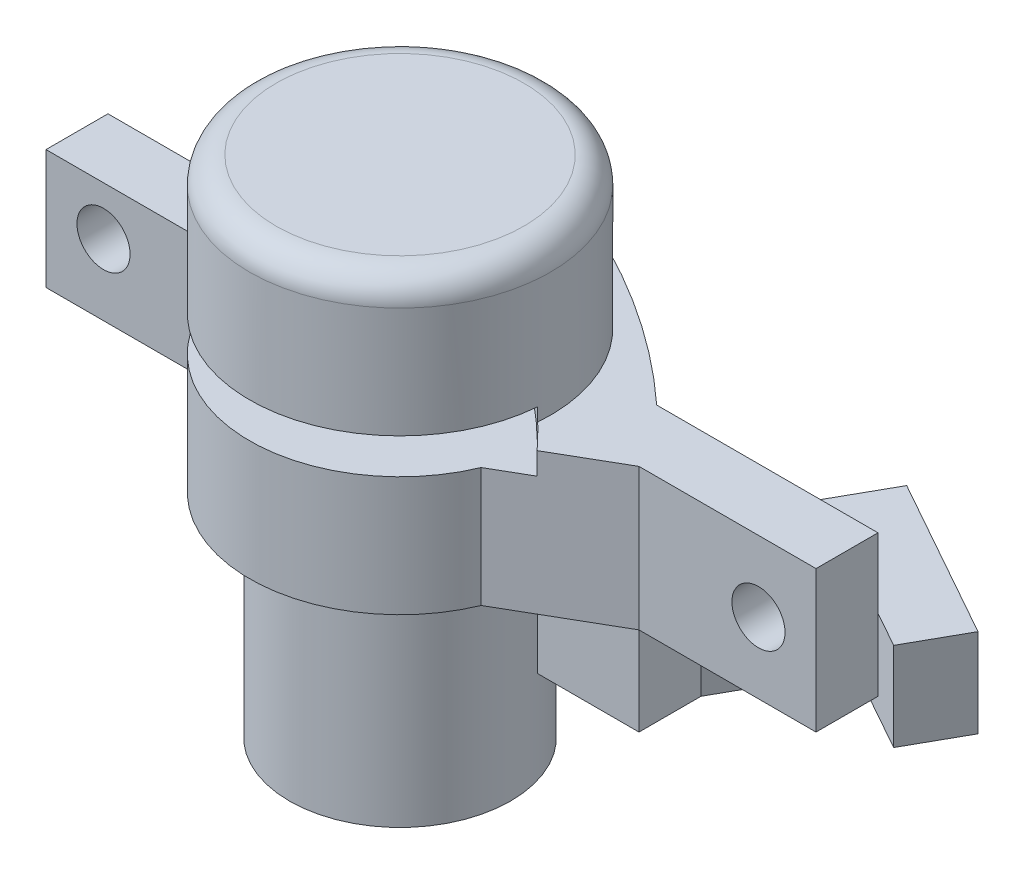
SolidWorks part; units mm, degrees
ref_plane "Front Plane" through (0, 0, 0) normal (0, 0, 1) x (1, 0, 0)
ref_plane "Top Plane" through (0, 0, 0) normal (0, 1, 0) x (1, 0, 0)
ref_plane "Right Plane" through (0, 0, 0) normal (1, 0, 0) x (0, 0, -1)
sketch "Sketch1" plane through (0, 0, 0) normal (0, 1, 0) x (1, 0, 0)
  line L0 (0, -55) -> (0, 55) construction
  line L2 (-55, 0) -> (55, 0) construction
  line L3 (0, 0) -> (23, 0)
  line L4 (0, 0) -> (0, 7)
  line L5 (0, 7) -> (22, 7)
  line L6 (22, 7) -> (20.8133, 20.5642)
  line L7 (87, 0) -> (87, 7)
  line L8 (55.6978, -6.5253) -> (67, 0)
  line L9 (67, 0) -> (87, 0)
  line L10 (87, 7) -> (62, 7)
  arc A0 (23, 0) -> (55.6978, -6.5253) centre (40, 0) ccw
  arc A1 (26.9971, 25.8532) -> (62, 7) centre (7.7519, -51.7975) cw
  arc A2 (26.9971, 25.8532) -> (20.8133, 20.5642) centre (25.7943, 21) ccw
  dimension "D1" = 34
  dimension "D7" = 80
  dimension "D8" = 5
  dimension "D2" = 40
  dimension "D3" = 87
  dimension "D4" = 7
  dimension "D5" = 30
  dimension "D6" = 20
  dimension "D9" = 21
  dimension "D10" = 85
  dimension "D11" = 22
  dimension "D12" = 25
extrude "Boss-Extrude1" add sketch "Sketch1" along normal blind 16
sketch "Sketch2" plane through (0, 16, 0) normal (0, 1, 0) x (1, 0, 0)
  circle A0 centre (40, 0) radius 17
extrude "Boss-Extrude2" add sketch "Sketch2" along normal blind 17
sketch "Sketch3" plane through (0, 0, 0) normal (0, -1, 0) x (1, 0, 0)
  circle A0 centre (40, 0) radius 12.5
  dimension "D1" = 25
extrude "Boss-Extrude3" add sketch "Sketch3" along normal blind 24
sketch "Sketch4" plane through (0, 0, -7) normal (0, 0, -1) x (-1, 0, 0)
  line L0 (-87, 8) -> (0, 8) construction
  line L1 (-87, 16) -> (-87, 0) construction
  line L2 (0, 23.65) -> (0, -23.65) construction
  circle A0 centre (-80.5, 8) radius 3
  circle A1 centre (-6.5, 8) radius 3
  dimension "D1" = 6
  dimension "D2" = 74
  dimension "D3" = 6.5
extrude "Cut-Extrude1" cut sketch "Sketch4" against normal through all
sketch "Sketch5" plane through (0, 0, 0) normal (0, 1, 0) x (1, 0, 0)
  line L0 (67, 7) -> (73.3028, 18.2502)
  line L1 (87, 7) -> (62, 7) construction
  line L3 (68, 29.2448) -> (55.5123, 6.9548)
  line L4 (55.5123, 6.9548) -> (55.5123, 0)
  line L5 (-31.35, 0) -> (31.35, 0) construction
  line L6 (55.5123, 0) -> (67, 0)
  line L7 (67, 0) -> (67, 7)
  line L8 (87, 0) -> (87, 7) construction
  line L10 (86.3208, 18.9808) -> (82.8994, 12.8738)
  line L11 (82.8994, 12.8738) -> (73.3028, 18.2502)
  line L12 (68, 29.2448) -> (86.3208, 18.9808)
  circle A0 centre (40, 0) radius 17 construction
  dimension "D1" = 7
  dimension "D2" = 21
  dimension "D3" = 12
  dimension "D4" = 20
  dimension "D5" = 19
  dimension "D6" = 10
extrude "Boss-Extrude5" add sketch "Sketch5" against normal blind 10
sketch "Sketch7" plane through (0, 13.5, 0) normal (0, 1, 0) x (1, 0, 0)
  circle A0 centre (-0.4, -60) radius 82
  arc A2 (26.6335, -135.294) -> (58.5192, -114.1159) centre (-0.4, -60) ccw construction
  dimension "D1" = 164
extrude "Cut-Extrude2" cut sketch "Sketch7" along normal blind 4
fillet "Fillet1" radius 3
